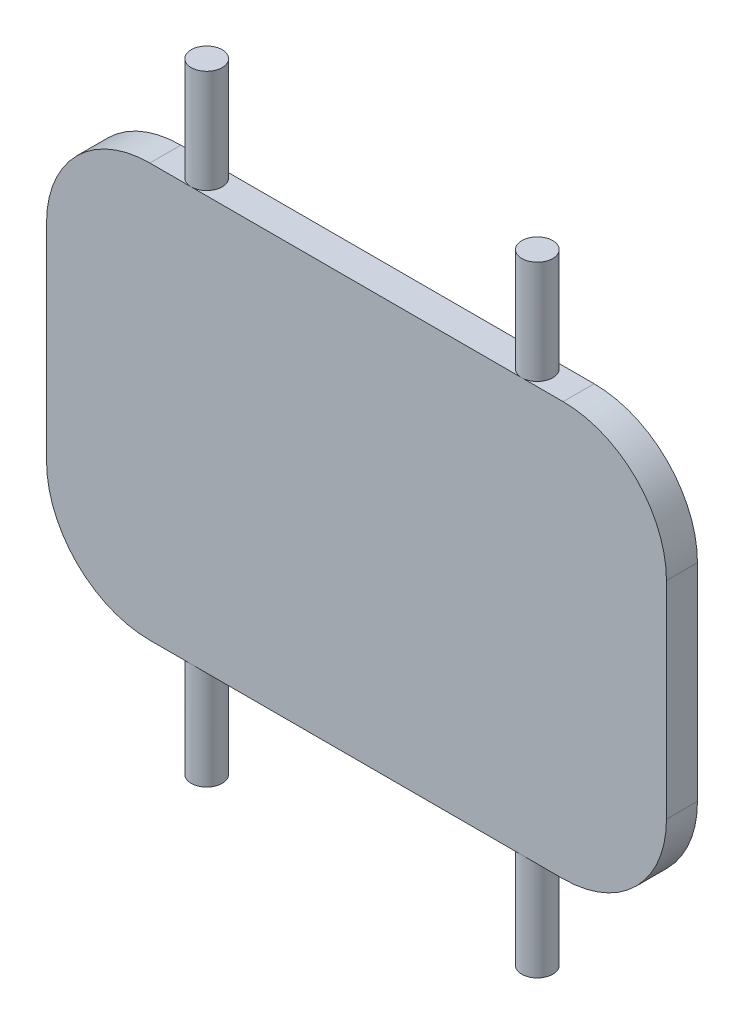
SolidWorks part; units mm, degrees
ref_plane "Front Plane" through (0, 0, 0) normal (0, 0, 1) x (1, 0, 0)
ref_plane "Top Plane" through (0, 0, 0) normal (0, 1, 0) x (1, 0, 0)
ref_plane "Right Plane" through (0, 0, 0) normal (1, 0, 0) x (0, 0, -1)
sketch "Sketch3" plane through (0, 0, 0) normal (0, 0, 1) x (1, 0, 0)
  line L5 (-150, 100) -> (150, 100)
  line L6 (-150, 100) -> (-150, -100)
  line L7 (-150, -100) -> (150, -100)
  line L8 (150, 100) -> (150, -100)
  line L9 (-150, 100) -> (150, -100) construction
  line L10 (-150, -100) -> (150, 100) construction
  point P4 (0, 0)
  dimension "D1" = 300
  dimension "D2" = 200
extrude "Boss-Extrude1" add sketch "Sketch3" along normal blind 15
fillet "Fillet1" radius 50 4 edges at (-150, 100, 7.5) (150, 100, 7.5) (150, -100, 7.5) (-150, -100, 7.5)
sketch "Sketch7" plane through (0, -100, 0) normal (0, -1, 0) x (1, 0, 0)
  line L0 (-100, 15) -> (100, 15) construction
  line L1 (100, 0) -> (100, 15) construction
  circle A0 centre (80, 7.5) radius 7.5
  dimension "D2" = 20
  dimension "D3" = 15
  dimension "D1" = 7.5
extrude "Boss-Extrude2" add sketch "Sketch7" along normal blind 50
mirror "Mirror1" about plane through (0, 0, 0) normal (1, 0, 0) of "Boss-Extrude2"
mirror "Mirror2" about plane through (0, 0, 0) normal (0, 1, 0) of "Mirror1", "Boss-Extrude2"
